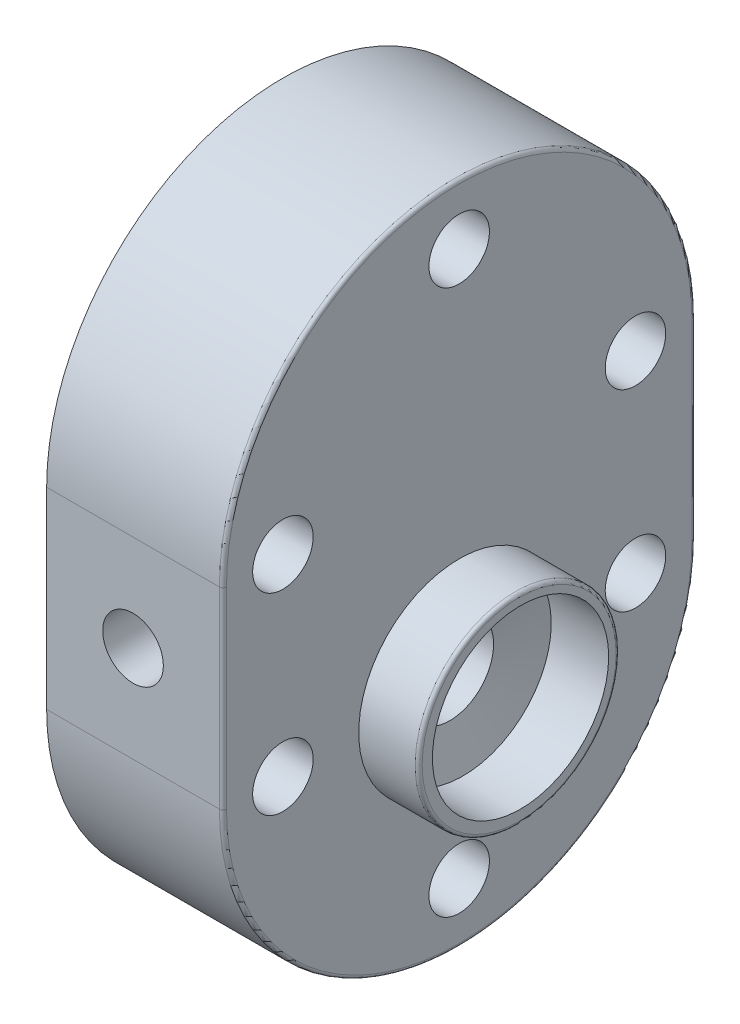
SolidWorks part; units mm, degrees
ref_plane "Front Plane" through (0, 0, 0) normal (0, 0, 1) x (1, 0, 0)
ref_plane "Top Plane" through (0, 0, 0) normal (0, 1, 0) x (1, 0, 0)
ref_plane "Right Plane" through (0, 0, 0) normal (1, 0, 0) x (0, 0, -1)
sketch "Sketch1" plane through (0, 0, 0) normal (1, 0, 0) x (0, 0, -1)
  line L0 (-85.1, 69.32) -> (-85.1, 0)
  line L1 (85.1, 69.32) -> (85.1, 0)
  arc A0 (85.1, 69.32) -> (-85.1, 69.32) centre (0, 69.32) ccw
  arc A1 (-85.1, 0) -> (85.1, 0) centre (0, 0) ccw
  dimension "D2" = 85.1
  dimension "D1" = 69.32
extrude "Boss-Extrude1" add sketch "Sketch1" against normal blind 63.5
sketch "Sketch2" plane through (0, 0, 0) normal (1, 0, 0) x (0, 0, -1)
  line L0 (-85.1, 34.66) -> (85.1, 34.66) construction
  line L1 (-85.1, 69.32) -> (-85.1, 0) construction
  line L2 (85.1, 0) -> (85.1, 69.32) construction
  line L3 (0, 154.42) -> (0, 34.66) construction
  arc A0 (85.1, 69.32) -> (-85.1, 69.32) centre (0, 69.32) ccw construction
  circle A1 centre (0, 132.83) radius 10.9
  circle A2 centre (63.5, 69.33) radius 10.9
  circle A3 centre (-63.5, 69.33) radius 10.9
  circle A4 centre (63.5, -0.01) radius 10.9
  circle A5 centre (-63.5, -0.01) radius 10.9
  circle A6 centre (0, -63.51) radius 10.9
  dimension "D2" = 21.8
  dimension "D1" = 63.5
  dimension "D3" = 63.5
  dimension "D4" = 69.34
extrude "Cut-Extrude1" cut sketch "Sketch2" against normal through all
sketch "Sketch3" plane through (-63.5, 0, 0) normal (-1, 0, 0) x (0, 0, 1)
  arc A0 (-20.9326, 34.671) -> (20.9326, 34.671) centre (0, 0) ccw
  arc A1 (20.9326, 34.671) -> (-20.9326, 34.671) centre (0, 69.342) ccw
  dimension "D2" = 81
  dimension "D1" = 69.342
extrude "Cut-Extrude2" cut sketch "Sketch3" against normal blind 38.1
sketch "Sketch5" plane through (0, 0, 0) normal (1, 0, 0) x (0, 0, -1)
  circle A0 centre (0, 0) radius 36.195
  dimension "D1" = 72.39
extrude "Boss-Extrude2" add sketch "Sketch5" along normal blind 21.59
hole_wizard "#97 (2.5) Diameter Hole2" positions "3DSketch5" profile "Sketch10" hole size "#97" standard "ANSI Inch"
sketch3d "3DSketch5"
  point P0 (0, 0, 0)
  point P4 (0, 0, 0)
  point P6 (0, 0, 0)
  point P8 (0, 0, 0)
  point P10 (0, 0, 0)
  point P12 (0, 0, 0)
  point P14 (0, 0, 0)
  point P18 (0, 0, 0)
  point P20 (21.59, 0.3813, -0.5155)
sketch "Sketch10" plane through (21.59, 0.3813, -0.5155) normal (0, 1, 0) x (0, 0, -1)
  line L0 (0, 0) -> (0, 29.2)
  line L1 (0, 29.2) -> (31.75, 20.6926)
  line L2 (31.75, 20.6926) -> (31.75, 0)
  line L5 (31.75, 0) -> (0, 0)
  line L10 (0, 29.2) -> (-31.75, 20.6926) construction
  line L11 (0, -6.35) -> (0, 107.95) construction
  dimension "Hole Dia." = 63.5
  dimension "Hole Depth" = 29.2
  dimension "Drill Angle" = 150
sketch "Sketch11" plane through (-25.4, 0, 0) normal (-1, 0, 0) x (0, 0, 1)
  circle A0 centre (0, 0) radius 15.875
  dimension "D1" = 31.75
extrude "Cut-Extrude3" cut sketch "Sketch11" against normal through all
hole_wizard "#97 (1.25) Diameter Hole4" positions "3DSketch8" profile "Sketch16" hole size "#97" standard "ANSI Inch"
sketch3d "3DSketch8"
  line L0 (-25.4, 69.342, 0) -> (-63.5, 69.342, 0) construction
  point P0 (-25.4, 69.342, 0)
sketch "Sketch16" plane through (-25.4, 69.342, 0) normal (0, 1, 0) x (0, 0, 1)
  line L0 (0, 0) -> (0, 13.5)
  line L1 (0, 13.5) -> (15.875, 9.2463)
  line L2 (15.875, 9.2463) -> (15.875, 0)
  line L5 (15.875, 0) -> (0, 0)
  line L10 (0, 13.5) -> (-15.875, 9.2463) construction
  line L11 (0, -6.35) -> (0, 107.95) construction
  dimension "Hole Dia." = 31.75
  dimension "Hole Depth" = 13.5
  dimension "Drill Angle" = 150
fillet "Fillet1" radius 1.27 5 edges at (0, 34.66, -85.1) (0, -85.1, 0) (0, 34.66, 85.1) (21.59, 0, -36.195) (0, 154.42, 0)
sketch "Sketch17" plane through (0, 0, -85.1) normal (0, 0, -1) x (-1, 0, 0)
  line L0 (32.385, 69.32) -> (32.385, 0) construction
  line L1 (63.5, 69.32) -> (1.27, 69.32) construction
  line L2 (63.5, 0) -> (1.27, 0) construction
  point P6 (32.385, 34.66)
hole_wizard "1/16 (0.86) Diameter Hole1" positions "3DSketch9" profile "Sketch18" hole size "1/16" standard "ANSI Inch"
sketch3d "3DSketch9"
  point P0 (-32.385, 34.66, -85.1)
sketch "Sketch18" plane through (-32.385, 34.66, -85.1) normal (1, 0, 0) x (0, 1, 0)
  line L0 (0, 0) -> (0, 69)
  line L1 (0, 69) -> (10.922, 66.0735)
  line L2 (10.922, 66.0735) -> (10.922, 0)
  line L5 (10.922, 0) -> (0, 0)
  line L10 (0, 69) -> (-10.922, 66.0735) construction
  line L11 (0, -6.35) -> (0, 107.95) construction
  dimension "Hole Dia." = 21.844
  dimension "Hole Depth" = 69
  dimension "Drill Angle" = 150
ref_plane "Plane1" through (0, 0, 0) normal (0, 0, -1) x (-1, 0, 0)
mirror "Mirror1" about plane through (0, 0, 0) normal (0, 0, -1) of "1/16 (0.86) Diameter Hole1"
hole_wizard "1/16 (1.25) Diameter Hole1" positions "3DSketch10" profile "Sketch19" hole size "1/16" standard "ANSI Inch"
sketch3d "3DSketch10"
  point P0 (-32.385, 34.66, -85.1)
sketch "Sketch19" plane through (-32.385, 34.66, -85.1) normal (1, 0, 0) x (0, 1, 0)
  line L0 (0, 0) -> (0, 43.2)
  line L1 (0, 43.2) -> (15.875, 38.9463)
  line L2 (15.875, 38.9463) -> (15.875, 0)
  line L5 (15.875, 0) -> (0, 0)
  line L10 (0, 43.2) -> (-15.875, 38.9463) construction
  line L11 (0, -6.35) -> (0, 107.95) construction
  dimension "Hole Dia." = 31.75
  dimension "Hole Depth" = 43.2
  dimension "Drill Angle" = 150
ref_plane "Plane2" through (-63.5, 34.671, 20.9326) normal (0, 0.5169, 0.8561) x (1, 0, 0)
